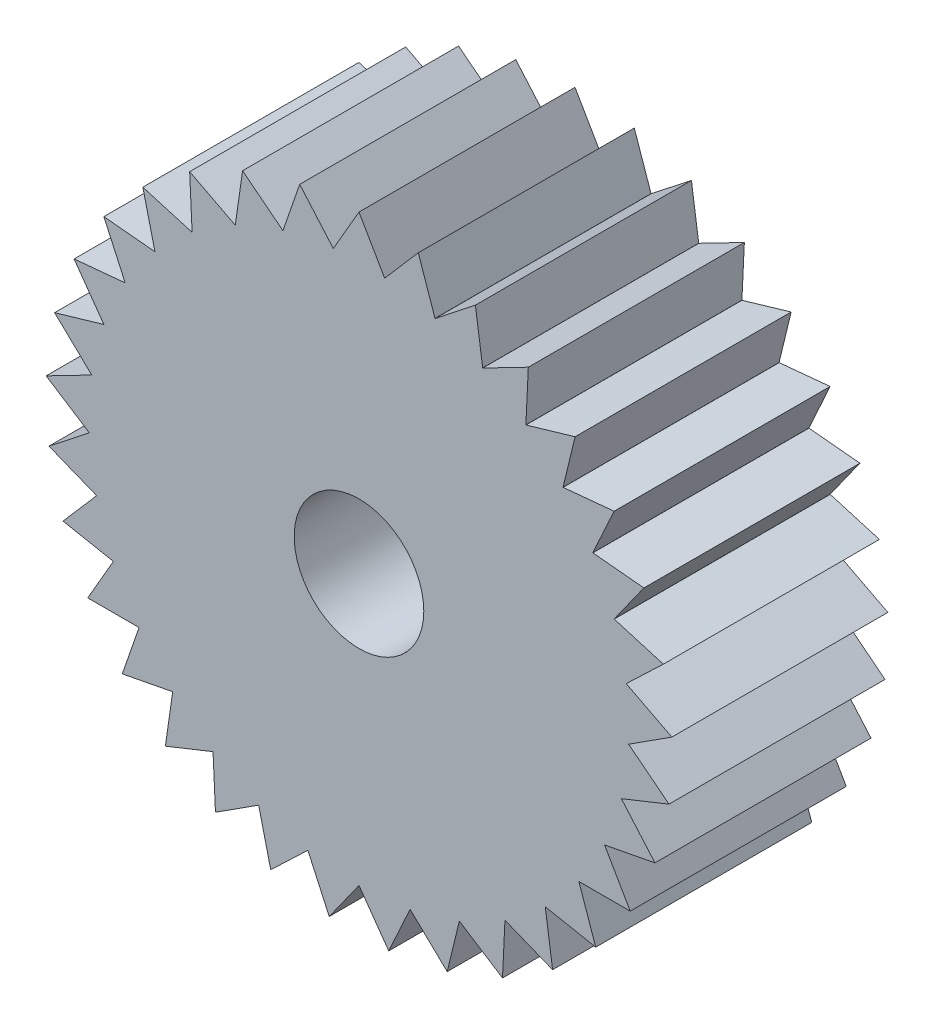
SolidWorks part; units mm, degrees
ref_plane "Front Plane" through (0, 0, 0) normal (0, 0, 1) x (1, 0, 0)
ref_plane "Top Plane" through (0, 0, 0) normal (0, 1, 0) x (1, 0, 0)
ref_plane "Right Plane" through (0, 0, 0) normal (1, 0, 0) x (0, 0, -1)
sketch "Sketch1" plane through (0, 0, 0) normal (0, 0, 1) x (1, 0, 0)
  line L2 (0, 14.4981) -> (1.1862, 12.4436)
  line L4 (1.1902, 12.4432) -> (2.7438, 14.2361)
  line L5 (-1.1862, 12.4436) -> (0, 14.4981)
  line L6 (2.7438, 14.2361) -> (3.5197, 11.9942)
  line L7 (3.5236, 11.9931) -> (5.3884, 13.4595)
  line L8 (5.3884, 13.4595) -> (5.726, 11.1114)
  line L9 (5.7297, 11.1095) -> (7.8383, 12.1966)
  line L10 (7.8383, 12.1966) -> (7.7254, 9.8269)
  line L11 (7.7286, 9.8244) -> (10.0048, 10.4928)
  line L12 (10.0048, 10.4928) -> (9.4455, 8.1873)
  line L13 (9.4482, 8.1842) -> (11.8098, 8.4097)
  line L14 (11.8098, 8.4097) -> (10.8243, 6.2518)
  line L15 (10.8263, 6.2482) -> (13.1879, 6.0227)
  line L16 (13.1879, 6.0227) -> (11.8118, 4.0903)
  line L17 (11.8132, 4.0864) -> (14.0894, 3.4181)
  line L18 (14.0894, 3.4181) -> (12.3725, 1.781)
  line L19 (12.3731, 1.7769) -> (14.4817, 0.6898)
  line L20 (14.4817, 0.6898) -> (12.4859, -0.5927)
  line L21 (12.4857, -0.5968) -> (14.3505, -2.0633)
  line L22 (14.3505, -2.0633) -> (12.1481, -2.945)
  line L23 (12.1472, -2.949) -> (13.7007, -4.7419)
  line L24 (13.7007, -4.7419) -> (11.3713, -5.1908)
  line L25 (11.3695, -5.1946) -> (12.5557, -7.249)
  line L26 (12.5557, -7.249) -> (10.1834, -7.249)
  line L27 (10.181, -7.2524) -> (10.9569, -9.4942)
  line L28 (10.9569, -9.4942) -> (8.6275, -9.0453)
  line L29 (8.6245, -9.0481) -> (8.9621, -11.3963)
  line L30 (8.9621, -11.3963) -> (6.7597, -10.5146)
  line L31 (6.7563, -10.5168) -> (6.6434, -12.8864)
  line L32 (6.6434, -12.8864) -> (4.6477, -11.6038)
  line L33 (4.6439, -11.6054) -> (4.0846, -13.9108)
  line L34 (4.0846, -13.9108) -> (2.3677, -12.2737)
  line L35 (2.3636, -12.2745) -> (1.3781, -14.4324)
  line L36 (1.3781, -14.4324) -> (0.0021, -12.5)
  line L37 (-0.0021, -12.5) -> (-1.3781, -14.4324)
  line L38 (-1.3781, -14.4324) -> (-2.3636, -12.2745)
  line L39 (-2.3677, -12.2737) -> (-4.0846, -13.9108)
  line L40 (-4.0846, -13.9108) -> (-4.6439, -11.6054)
  line L41 (-4.6477, -11.6038) -> (-6.6434, -12.8864)
  line L42 (-6.6434, -12.8864) -> (-6.7563, -10.5168)
  line L43 (-6.7597, -10.5146) -> (-8.9621, -11.3963)
  line L44 (-8.9621, -11.3963) -> (-8.6245, -9.0481)
  line L45 (-8.6275, -9.0453) -> (-10.9569, -9.4942)
  line L46 (-10.9569, -9.4942) -> (-10.181, -7.2524)
  line L47 (-10.1834, -7.249) -> (-12.5557, -7.249)
  line L48 (-12.5557, -7.249) -> (-11.3695, -5.1946)
  line L49 (-11.3713, -5.1908) -> (-13.7007, -4.7419)
  line L50 (-13.7007, -4.7419) -> (-12.1472, -2.949)
  line L51 (-12.1481, -2.945) -> (-14.3505, -2.0633)
  line L52 (-14.3505, -2.0633) -> (-12.4857, -0.5968)
  line L53 (-12.4859, -0.5927) -> (-14.4817, 0.6898)
  line L54 (-14.4817, 0.6898) -> (-12.3731, 1.7769)
  line L55 (-12.3725, 1.781) -> (-14.0894, 3.4181)
  line L56 (-14.0894, 3.4181) -> (-11.8132, 4.0864)
  line L57 (-11.8118, 4.0903) -> (-13.1879, 6.0227)
  line L58 (-13.1879, 6.0227) -> (-10.8263, 6.2482)
  line L59 (-10.8243, 6.2518) -> (-11.8098, 8.4097)
  line L60 (-11.8098, 8.4097) -> (-9.4482, 8.1842)
  line L61 (-9.4455, 8.1873) -> (-10.0048, 10.4928)
  line L62 (-10.0048, 10.4928) -> (-7.7286, 9.8244)
  line L63 (-7.7254, 9.8269) -> (-7.8383, 12.1966)
  line L64 (-7.8383, 12.1966) -> (-5.7297, 11.1095)
  line L65 (-5.726, 11.1114) -> (-5.3884, 13.4595)
  line L66 (-5.3884, 13.4595) -> (-3.5236, 11.9931)
  line L67 (-3.5197, 11.9942) -> (-2.7438, 14.2361)
  line L68 (-2.7438, 14.2361) -> (-1.1902, 12.4432)
  arc A0 (-1.1862, 12.4436) -> (-1.1902, 12.4432) centre (0, 0) ccw
  circle A1 centre (0, 0) radius 3
  arc A2 (-3.5197, 11.9942) -> (-3.5236, 11.9931) centre (0, 0) ccw
  arc A3 (-5.726, 11.1114) -> (-5.7297, 11.1095) centre (0, 0) ccw
  arc A4 (-7.7254, 9.8269) -> (-7.7286, 9.8244) centre (0, 0) ccw
  arc A5 (-9.4455, 8.1873) -> (-9.4482, 8.1842) centre (0, 0) ccw
  arc A6 (-10.8243, 6.2518) -> (-10.8263, 6.2482) centre (0, 0) ccw
  arc A7 (1.1902, 12.4432) -> (1.1862, 12.4436) centre (0, 0) ccw
  arc A8 (3.5236, 11.9931) -> (3.5197, 11.9942) centre (0, 0) ccw
  arc A9 (5.7297, 11.1095) -> (5.726, 11.1114) centre (0, 0) ccw
  arc A10 (7.7286, 9.8244) -> (7.7254, 9.8269) centre (0, 0) ccw
  arc A11 (-11.8118, 4.0903) -> (-11.8132, 4.0864) centre (0, 0) ccw
  arc A12 (-12.3725, 1.781) -> (-12.3731, 1.7769) centre (0, 0) ccw
  arc A13 (-12.4859, -0.5927) -> (-12.4857, -0.5968) centre (0, 0) ccw
  arc A14 (-12.1481, -2.945) -> (-12.1472, -2.949) centre (0, 0) ccw
  arc A15 (-11.3713, -5.1908) -> (-11.3695, -5.1946) centre (0, 0) ccw
  arc A16 (-10.1834, -7.249) -> (-10.181, -7.2524) centre (0, 0) ccw
  arc A17 (-8.6275, -9.0453) -> (-8.6245, -9.0481) centre (0, 0) ccw
  arc A18 (9.4482, 8.1842) -> (9.4455, 8.1873) centre (0, 0) ccw
  arc A19 (10.8263, 6.2482) -> (10.8243, 6.2518) centre (0, 0) ccw
  arc A20 (11.8132, 4.0864) -> (11.8118, 4.0903) centre (0, 0) ccw
  arc A21 (12.3731, 1.7769) -> (12.3725, 1.781) centre (0, 0) ccw
  arc A22 (12.4857, -0.5968) -> (12.4859, -0.5927) centre (0, 0) ccw
  arc A23 (12.1472, -2.949) -> (12.1481, -2.945) centre (0, 0) ccw
  arc A24 (11.3695, -5.1946) -> (11.3713, -5.1908) centre (0, 0) ccw
  arc A25 (10.181, -7.2524) -> (10.1834, -7.249) centre (0, 0) ccw
  arc A26 (-6.7597, -10.5146) -> (-6.7563, -10.5168) centre (0, 0) ccw
  arc A27 (-4.6477, -11.6038) -> (-4.6439, -11.6054) centre (0, 0) ccw
  arc A28 (-2.3677, -12.2737) -> (-2.3636, -12.2745) centre (0, 0) ccw
  arc A29 (-0.0021, -12.5) -> (0.0021, -12.5) centre (0, 0) ccw
  arc A30 (2.3636, -12.2745) -> (2.3677, -12.2737) centre (0, 0) ccw
  arc A31 (4.6439, -11.6054) -> (4.6477, -11.6038) centre (0, 0) ccw
  arc A32 (6.7563, -10.5168) -> (6.7597, -10.5146) centre (0, 0) ccw
  arc A33 (8.6245, -9.0481) -> (8.6275, -9.0453) centre (0, 0) ccw
  dimension "D3" = 33
extrude "Boss-Extrude1" add sketch "Sketch1" along normal blind 10
